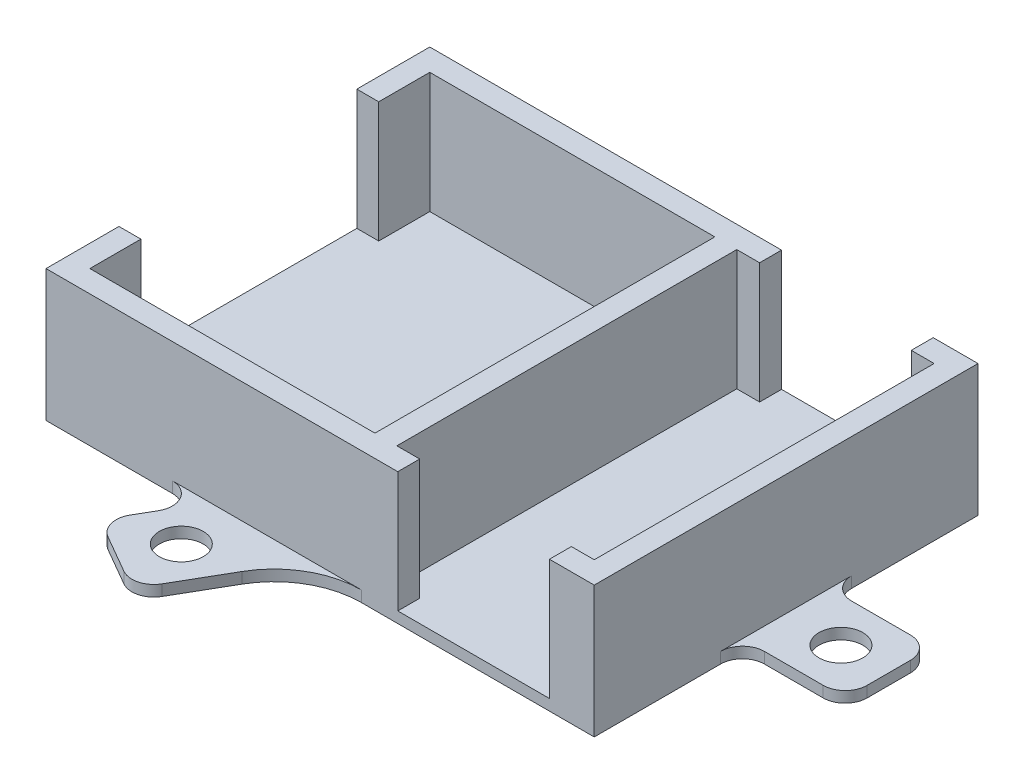
SolidWorks part; units mm, degrees
ref_plane "Front Plane" through (0, 0, 0) normal (0, 0, 1) x (1, 0, 0)
ref_plane "Top Plane" through (0, 0, 0) normal (0, 1, 0) x (1, 0, 0)
ref_plane "Right Plane" through (0, 0, 0) normal (1, 0, 0) x (0, 0, -1)
sketch "Sketch1" plane through (0, 0, 0) normal (0, 1, 0) x (1, 0, 0)
  line L0 (-0.9264, 0) -> (0, 0) construction
  line L1 (-26.9264, -15.5) -> (-0.9264, -15.5)
  line L2 (-26.9264, -15.5) -> (-26.9264, -10.8467)
  line L3 (-26.9264, 15.5) -> (-0.9264, 15.5)
  line L4 (-0.9264, -15.5) -> (-0.9264, 15.5)
  line L5 (0, 0) -> (1.0736, 0) construction
  line L6 (1.0736, 15.5) -> (3.1574, 15.5)
  line L7 (1.0736, 15.5) -> (1.0736, -15.5)
  line L8 (1.0736, -15.5) -> (3.1574, -15.5)
  line L9 (19.0736, 15.5) -> (19.0736, -15.5)
  line L10 (-26.9264, -15.5) -> (19.0736, 15.5) construction
  line L11 (-28.9264, 10.8467) -> (-26.9264, 10.8467)
  line L12 (-28.9264, -17.5) -> (3.1574, -17.5)
  line L13 (-28.9264, -17.5) -> (-28.9264, -10.8467)
  line L14 (-28.9264, 17.5) -> (3.1574, 17.5)
  line L15 (21.0736, -17.5) -> (21.0736, 17.5)
  line L16 (-28.9264, -17.5) -> (21.0736, 17.5) construction
  line L17 (-28.9264, 17.5) -> (21.0736, -17.5) construction
  line L18 (-3.9264, 0) -> (-26.9264, 0) construction
  line L19 (-28.9264, -10.8467) -> (-26.9264, -10.8467)
  line L20 (-28.9264, 10.8467) -> (-28.9264, 17.5)
  line L21 (-26.9264, 10.8467) -> (-26.9264, 15.5)
  line L22 (10.0736, 15.5) -> (10.0736, 17.5) construction
  line L23 (3.1574, 17.5) -> (3.1574, 15.5)
  line L24 (16.9897, 17.5) -> (16.9897, 15.5)
  line L25 (16.9897, -17.5) -> (16.9897, -15.5)
  line L26 (3.1574, -17.5) -> (3.1574, -15.5)
  line L27 (16.9897, -17.5) -> (21.0736, -17.5)
  line L28 (16.9897, -15.5) -> (19.0736, -15.5)
  line L29 (16.9897, 15.5) -> (19.0736, 15.5)
  line L30 (16.9897, 17.5) -> (21.0736, 17.5)
  point P6 (-3.9264, 0)
  dimension "D1" = 2
  dimension "D2" = 31
  dimension "D3" = 26
  dimension "D4" = 18
  dimension "D5" = 2
  dimension "D6" = 2
extrude "Boss-Extrude1" add sketch "Sketch1" along normal blind 11
sketch "Sketch2" plane through (0, 0, 0) normal (0, -1, 0) x (1, 0, 0)
  line L0 (21.0736, 0) -> (26.0736, 0) construction
  line L1 (-28.9264, 17.5) -> (-17.4083, 17.5)
  line L2 (-28.9264, 17.5) -> (-28.9264, -17.5)
  line L3 (-28.9264, -17.5) -> (-17.5892, -17.5)
  line L4 (21.0736, 17.5) -> (21.0736, 5.9766)
  line L5 (23.0736, -3.9766) -> (28.4347, -3.9766)
  line L6 (30.4347, -1.9766) -> (30.4347, 1.9766)
  line L7 (23.0736, 3.9766) -> (28.4347, 3.9766)
  line L8 (21.0736, -5.9766) -> (21.0736, -17.5)
  line L9 (-7.1469, -21.32) -> (-9.8274, -25.9628)
  line L10 (-15.9831, -24.7182) -> (-12.5595, -26.6949)
  line L11 (-15.8571, -20.5) -> (-16.7152, -21.9862)
  line L12 (-15.6762, 20.5) -> (-16.6247, 22.1429)
  line L13 (-12.469, 26.8516) -> (-15.8927, 24.8749)
  line L14 (-7.0564, 21.4766) -> (-9.737, 26.1195)
  line L15 (-28.9264, 17.5) -> (3.1574, 17.5) construction
  line L16 (-0.1687, 17.5) -> (21.0736, 17.5)
  line L17 (-0.8649, -17.5) -> (21.0736, -17.5)
  circle A0 centre (26.0736, 0) radius 2
  arc A1 (28.4347, -3.9766) -> (30.4347, -1.9766) centre (28.4347, -1.9766) ccw
  arc A2 (28.4347, 3.9766) -> (30.4347, 1.9766) centre (28.4347, 1.9766) cw
  arc A3 (23.0736, -3.9766) -> (21.0736, -5.9766) centre (23.0736, -5.9766) ccw
  arc A4 (23.0736, 3.9766) -> (21.0736, 5.9766) centre (23.0736, 5.9766) cw
  circle A5 centre (-12.0908, -21.9297) radius 2
  arc A6 (-9.8274, -25.9628) -> (-12.5595, -26.6949) centre (-11.5595, -24.9628) cw
  arc A7 (-16.7152, -21.9862) -> (-15.9831, -24.7182) centre (-14.9831, -22.9862) ccw
  circle A8 centre (-12.0003, 22.0864) radius 2
  arc A9 (-16.6247, 22.1429) -> (-15.8927, 24.8749) centre (-14.8927, 23.1429) cw
  arc A10 (-9.737, 26.1195) -> (-12.469, 26.8516) centre (-11.469, 25.1195) ccw
  arc A11 (-7.0564, 21.4766) -> (-0.1687, 17.5) centre (-0.1687, 25.4533) ccw
  arc A12 (-7.1469, -21.32) -> (-0.8649, -17.5) centre (-0.5168, -25.1479) cw
  arc A13 (-17.4083, 17.5) -> (-15.6762, 20.5) centre (-17.4083, 19.5) ccw
  arc A14 (-15.8571, -20.5) -> (-17.5892, -17.5) centre (-17.5892, -19.5) ccw
  point P14 (30.4347, 0)
  point P17 (30.4347, -3.9766)
  point P20 (30.4347, 3.9766)
  point P23 (21.0736, -3.9766)
  point P26 (21.0736, 3.9766)
  point P49 (0.6608, 0.0522)
  point P54 (0, 0)
  point P55 (0, 0)
  point P59 (-13.9442, 17.5)
  dimension "D1" = 2
  dimension "D3" = 2
  dimension "D5" = 2
  dimension "D2" = 5
  dimension "D4" = 3
extrude "Boss-Extrude2" add sketch "Sketch2" along normal blind 1
